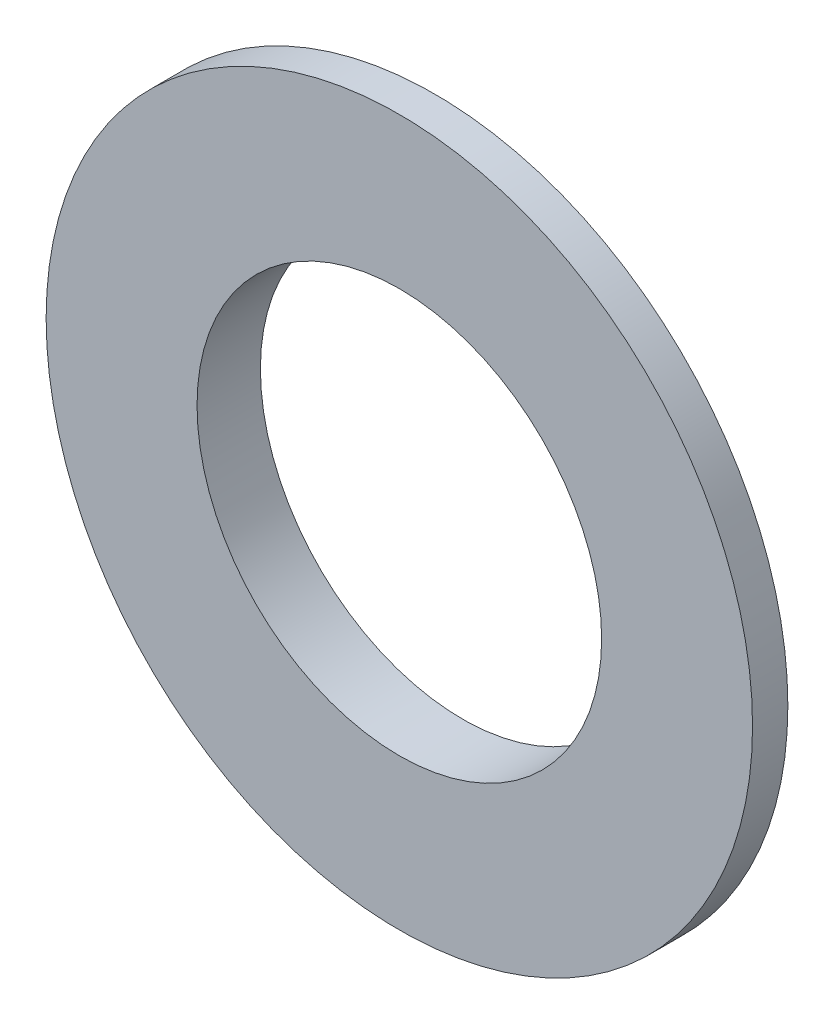
SolidWorks part; units mm, degrees
material "Custom Plastic"
ref_plane "X-Y Datum" through (0, 0, 0) normal (0, 0, 1) x (1, 0, 0)
ref_plane "X-Z Datum" through (0, 0, 0) normal (0, 1, 0) x (1, 0, 0)
ref_plane "Y-Z Datum" through (0, 0, 0) normal (1, 0, 0) x (0, 0, -1)
sketch "Sketch1" plane through (0, 0, 0) normal (0, 0, 1) x (1, 0, 0)
  circle A0 centre (0, 0) radius 11.455
  circle A1 centre (0, 0) radius 15 construction
  circle A3 centre (0, 0) radius 20
  circle A4 centre (0, 0) radius 14.619
  dimension "D1" = 22.91
  dimension "D2" = 30
  dimension "D3" = 40
  dimension "D4" = 0.381
extrude "Boss-Extrude1" add sketch "Sketch1" along normal blind 2 contours A4 A0 | A3 A4
sketch "Sketch2" plane through (0, 0, 0) normal (0, 0, -1) x (-1, 0, 0)
  circle A1 centre (0, 0) radius 14.619
  circle A2 centre (0, 0) radius 14.619
  circle A3 centre (0, 0) radius 20
  circle A4 centre (0, 0) radius 20
  circle A5 centre (0, 0) radius 11.455
  circle A6 centre (0, 0) radius 11.455
  circle M4 centre (0, 0) radius 11.455
  dimension "D1" = 0
  dimension "D2" = 0
  dimension "D3" = 0
extrude "Boss-Extrude2" add sketch "Sketch2" along normal blind 1.5875 contours A2 M4
